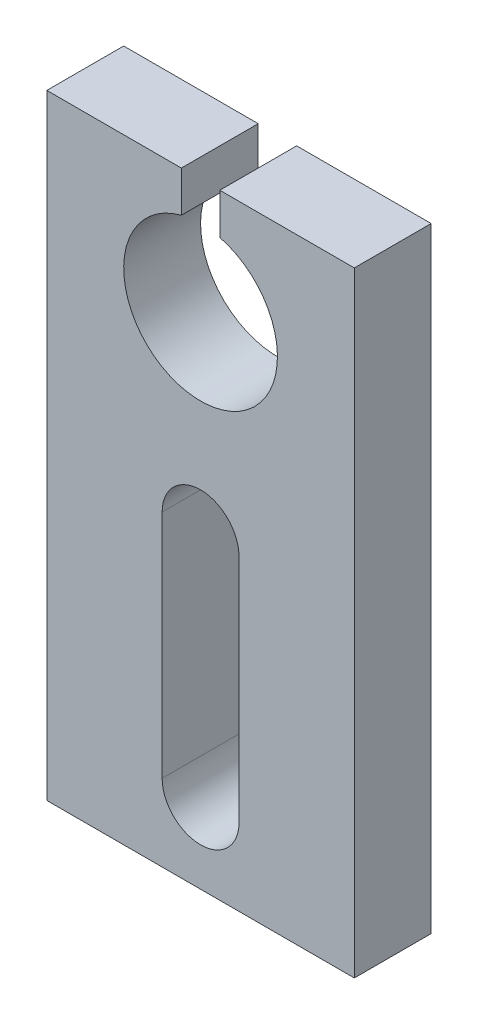
SolidWorks part; units mm, degrees
material "6061 Alloy"
ref_plane "Front Plane" through (0, 0, 0) normal (0, 0, 1) x (1, 0, 0)
ref_plane "Top Plane" through (0, 0, 0) normal (0, 1, 0) x (1, 0, 0)
ref_plane "Right Plane" through (0, 0, 0) normal (1, 0, 0) x (0, 0, -1)
sketch "Sketch1" plane through (0, 0, 0) normal (0, 0, 1) x (1, 0, 0)
  line L1 (-12.7, -25.4) -> (12.7, -25.4)
  line L2 (-12.7, -25.4) -> (-12.7, 25.4)
  line L3 (-12.7, 25.4) -> (12.7, 25.4)
  line L4 (12.7, -25.4) -> (12.7, 25.4)
  line L5 (-12.7, -25.4) -> (12.7, 25.4) construction
  line L6 (-12.7, 25.4) -> (12.7, -25.4) construction
  point P0 (0, 0)
  dimension "D1" = 50.8
  dimension "D2" = 25.4
extrude "Boss-Extrude1" add sketch "Sketch1" along normal blind 6.35
sketch "Sketch2" plane through (0, 0, 6.35) normal (0, 0, 1) x (1, 0, 0)
  line L1 (-1.5875, 14.4402) -> (1.5875, 14.4402)
  line L2 (-1.5875, 14.4402) -> (-1.5875, 25.4)
  line L3 (-1.5875, 25.4) -> (1.5875, 25.4)
  line L4 (1.5875, 14.4402) -> (1.5875, 25.4)
  line L5 (12.7, 25.4) -> (-12.7, 25.4) construction
  circle A0 centre (0, 15.875) radius 6.35
  line M4 (12.7, 25.4) -> (-12.7, 25.4)
  dimension "D2" = 12.7
  dimension "D1" = 15.875
  dimension "D3" = 1.5875
  dimension "D4" = 3.175
  dimension "D5" = 0
  dimension "D6" = 0
extrude "Cut-Extrude1" cut sketch "Sketch2" against normal through all contours L2 A0 L4 L1 | L4 A0 L2 L1 | A0 L4 L2 M4
sketch "Sketch3" plane through (0, 0, 6.35) normal (0, 0, 1) x (1, 0, 0)
  line L0 (0, -19.05) -> (0, 0) construction
  line L1 (-3.175, -19.05) -> (-3.175, 0)
  line L2 (3.175, -19.05) -> (3.175, 0)
  line L3 (-12.7, -25.4) -> (12.7, -25.4) construction
  arc A0 (-3.175, -19.05) -> (3.175, -19.05) centre (0, -19.05) ccw
  arc A1 (3.175, 0) -> (-3.175, 0) centre (0, 0) ccw
  point P3 (0, -9.525)
  dimension "D1" = 6.35
  dimension "D2" = 19.05
  dimension "D3" = 6.35
extrude "Cut-Extrude2" cut sketch "Sketch3" against normal through all
